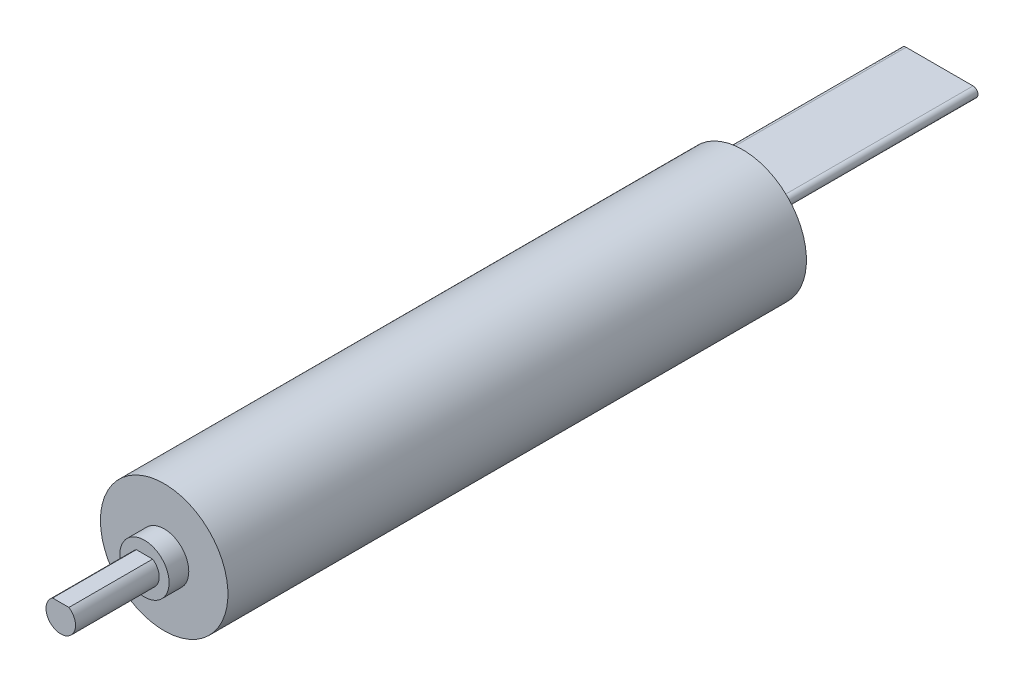
SolidWorks part; units mm, degrees
ref_plane "Front Plane" through (0, 0, 0) normal (0, 0, 1) x (1, 0, 0)
ref_plane "Top Plane" through (0, 0, 0) normal (0, 1, 0) x (1, 0, 0)
ref_plane "Right Plane" through (0, 0, 0) normal (1, 0, 0) x (0, 0, -1)
sketch "Sketch1" plane through (0, 0, 0) normal (0, 0, 1) x (1, 0, 0)
  circle A0 centre (0, 0) radius 6.475
  dimension "D1" = 12.95
extrude "Boss-Extrude1" add sketch "Sketch1" along normal blind 58.75
sketch "Sketch2" plane through (0, 0, 58.75) normal (0, 0, 1) x (1, 0, 0)
  circle A0 centre (0, 0) radius 2.5
  dimension "D1" = 5
extrude "Boss-Extrude2" add sketch "Sketch2" along normal blind 2
sketch "Sketch3" plane through (0, 0, 60.75) normal (0, 0, 1) x (1, 0, 0)
  line L0 (-1.4507, 1.25) -> (2.6841, 1.25)
  line L1 (0, 1.25) -> (0, -1.5) construction
  circle A0 centre (0, 0) radius 1.5
  dimension "D1" = 3
  dimension "D2" = 2.75
extrude "Boss-Extrude3" add sketch "Sketch3" along normal blind 8.5 contours L1 L0 A0 | L0 L1 A0
sketch "Sketch4" plane through (0, 0, 0) normal (0, 0, -1) x (-1, 0, 0)
  line L0 (0, 6.475) -> (0, -6.475) construction
  line L1 (-6.475, 0) -> (6.475, 0) construction
  line L2 (-3.4, 3.275) -> (3.4, 3.275) construction
  line L3 (-3.4, 3.775) -> (3.4, 3.775)
  line L4 (-3.4, 2.775) -> (3.4, 2.775)
  circle A0 centre (0, 0) radius 6.475 construction
  arc A1 (-3.4, 3.775) -> (-3.4, 2.775) centre (-3.4, 3.275) ccw
  arc A2 (3.4, 2.775) -> (3.4, 3.775) centre (3.4, 3.275) ccw
  point P9 (0, 3.275)
  point P14 (-3.9, 3.275)
  point P15 (3.9, 3.275)
  dimension "D1" = 7.8
  dimension "D2" = 1
  dimension "D3" = 10.25
extrude "Boss-Extrude4" add sketch "Sketch4" along normal blind 20
